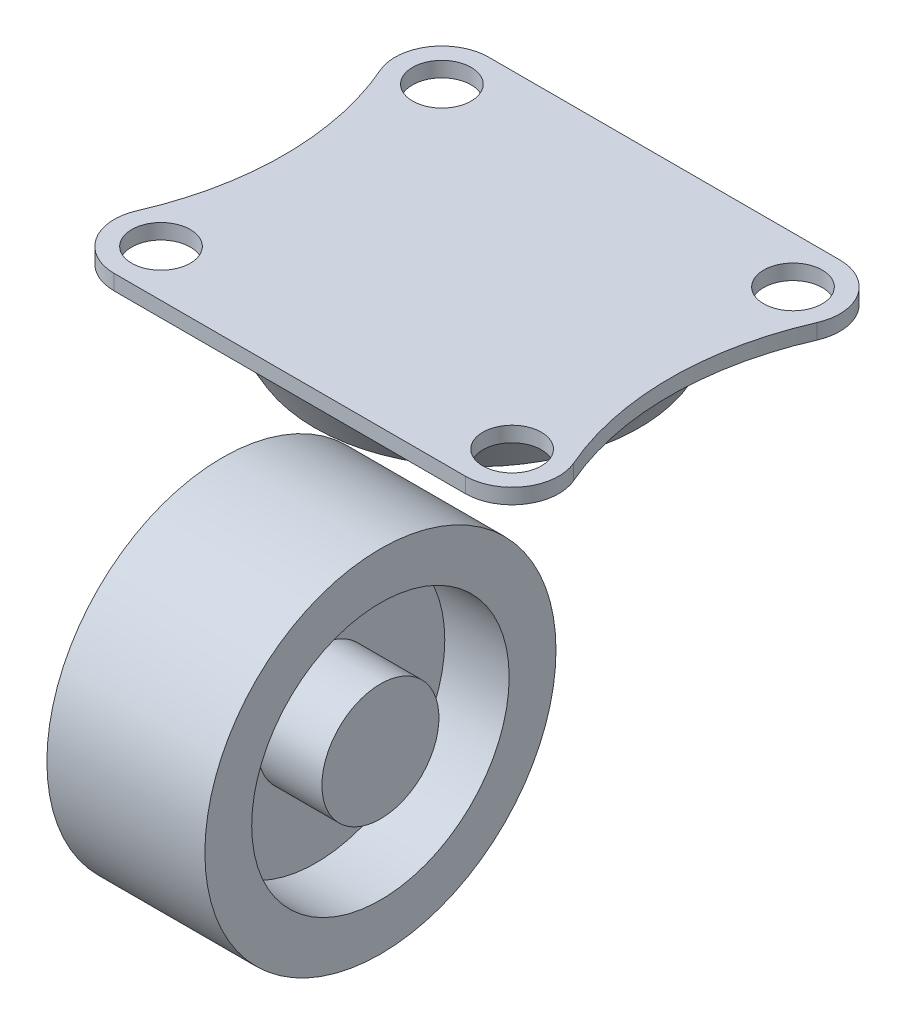
SolidWorks part; units mm, degrees
ref_plane "Front Plane" through (0, 0, 0) normal (0, 0, 1) x (1, 0, 0)
ref_plane "Top Plane" through (0, 0, 0) normal (0, 1, 0) x (1, 0, 0)
ref_plane "Right Plane" through (0, 0, 0) normal (1, 0, 0) x (0, 0, -1)
sketch "Sketch1" plane through (0, 0, 0) normal (0, 1, 0) x (1, 0, 0)
  line L0 (0, -16) -> (0, 16) construction
  line L1 (-15, 16) -> (15, 16)
  line L3 (-15, -16) -> (15, -16)
  line L5 (-19, 16) -> (19, -16) construction
  line L6 (-19, -16) -> (19, 16) construction
  line L7 (19, 0) -> (-19, 0) construction
  circle A0 centre (0, 0) radius 16 construction
  circle A1 centre (-15, 12) radius 2.5
  circle A2 centre (15, 12) radius 2.5
  circle A3 centre (15, -12) radius 2.5
  circle A4 centre (-15, -12) radius 2.5
  arc A9 (-18.6672, -10.4027) -> (-15, -16) centre (-15, -12) ccw
  arc A10 (-15, 16) -> (-18.6672, 10.4027) centre (-15, 12) ccw
  arc A12 (18.6672, 10.4027) -> (15, 16) centre (15, 12) ccw
  arc A13 (-18.6672, -10.4027) -> (-18.6672, 10.4027) centre (-42.55, 0) ccw
  arc A14 (18.6672, -10.4027) -> (18.6672, 10.4027) centre (42.55, 0) cw
  arc A15 (15, -16) -> (18.6672, -10.4027) centre (15, -12) ccw
  point P0 (0, 0)
  point P33 (-16, 0)
  point P37 (-16.5, 0)
  point P38 (0, 0)
  dimension "D3" = 5
  dimension "D1" = 32
  dimension "D2" = 38
  dimension "D6" = 0.5
extrude "Boss-Extrude1" add sketch "Sketch1" along normal blind 1.3
sketch "Sketch2" plane through (0, 0, 0) normal (0, -1, 0) x (1, 0, 0)
  circle A0 centre (0, 0) radius 16
extrude "Boss-Extrude2" add sketch "Sketch2" along normal blind 3.7 draft 30
ref_plane "Plane1" through (0, -23.7, 0) normal (0, -1, 0) x (-1, 0, 0)
sketch "Sketch4" plane through (0, -23.7, 0) normal (0, -1, 0) x (-1, 0, 0)
  line L0 (7.6367, -15) -> (-7.2716, -15) construction
  line L1 (0, 0) -> (0, -15) construction
  line L3 (6.75, 0) -> (6.75, -4)
  line L4 (6.75, -4) -> (1.25, -4)
  line L5 (1.25, -4) -> (1.25, -10)
  line L6 (1.25, -10) -> (6.75, -10)
  line L7 (6.75, -10) -> (6.75, -15)
  line L8 (-6.75, -10) -> (-6.75, -15)
  line L9 (-1.25, -10) -> (-6.75, -10)
  line L15 (6.75, 0) -> (-6.75, 0)
  line L16 (-6.75, 0) -> (-6.75, -4)
  line L17 (-6.75, -4) -> (-1.25, -4)
  line L18 (-1.25, -4) -> (-1.25, -10)
  line L19 (6.75, -15) -> (-6.75, -15)
  dimension "D3" = 4
  dimension "D4" = 5.5
  dimension "D6" = 5
revolve "Revolve1" add sketch "Sketch4" angle 360 about L0
